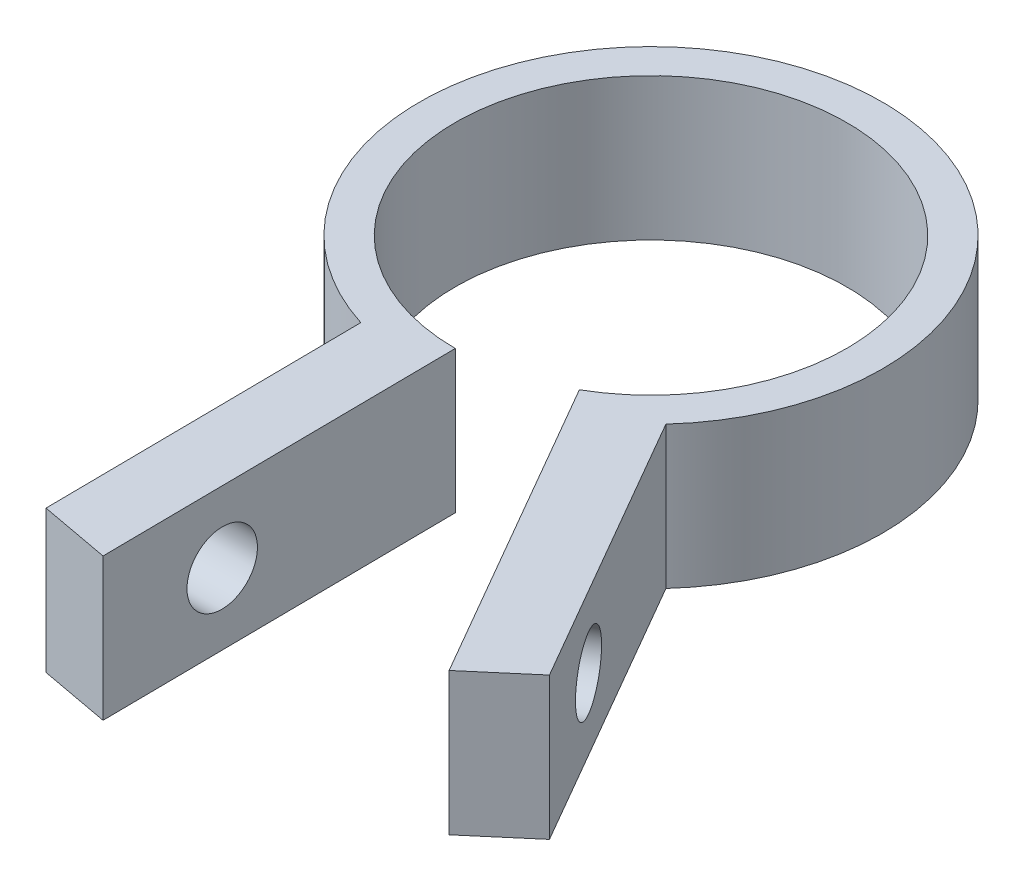
SolidWorks part; units mm, degrees
material "ABS"
ref_plane "Front Plane" through (0, 0, 0) normal (0, 0, 1) x (1, 0, 0)
ref_plane "Top Plane" through (0, 0, 0) normal (0, 1, 0) x (1, 0, 0)
ref_plane "Right Plane" through (0, 0, 0) normal (1, 0, 0) x (0, 0, -1)
sketch "Sketch2" plane through (0, 0, 0) normal (0, 1, 0) x (1, 0, 0)
  line L0 (0, 0) -> (0, -6.5)
  line L1 (0, 0) -> (3.25, -5.6292)
  line L3 (0, -5.5) -> (-1.9667, -5.1364)
  line L4 (0, -5.5) -> (0.1015, -15.4995)
  line L5 (0.1015, -15.4995) -> (-1.8652, -15.1358)
  line L6 (-1.9667, -5.1364) -> (-1.8652, -15.1358)
  line L7 (2.75, -4.7631) -> (4.2714, -3.4649)
  line L8 (2.75, -4.7631) -> (7.75, -13.4234)
  line L9 (7.75, -13.4234) -> (9.2714, -12.1251)
  line L10 (4.2714, -3.4649) -> (9.2714, -12.1251)
  arc A0 (3.25, -5.6292) -> (0, -6.5) centre (0, 0) ccw
  arc A1 (2.75, -4.7631) -> (0, -5.5) centre (0, 0) ccw
  dimension "D1" = 13
  dimension "D2" = 11
  dimension "D3" = 30
  dimension "D4" = 2
  dimension "D5" = 2
  dimension "D6" = 10
  dimension "D7" = 10
extrude "Boss-Extrude1" add sketch "Sketch2" along normal blind 4 contours A1 L10 A0 L6 | A1 L6 A0 L0 | A1 L1 A0 L10 | A0 L8 L9 L10 | A0 L6 L5 L4 L0
sketch "Sketch3" plane through (-2.0186, 0, 0.0205) normal (-0.9999, 0, 0.0101) x (0.0101, 0, 0.9999)
  line L0 (15.1161, 4) -> (15.1161, 0) construction
  circle A0 centre (12.1161, 2) radius 1
  dimension "D1" = 2
  dimension "D2" = 3
extrude "Cut-Extrude1" cut sketch "Sketch3" against normal up to next
sketch "Sketch5" plane through (1.7032, 0, -0.9833) normal (0.866, 0, -0.5) x (-0.5, 0, -0.866)
  line L0 (-15.1364, 4) -> (-15.1364, 0) construction
  circle A0 centre (-12.1364, 2) radius 1
  dimension "D1" = 2
  dimension "D2" = 3
extrude "Cut-Extrude2" cut sketch "Sketch5" against normal up to next
